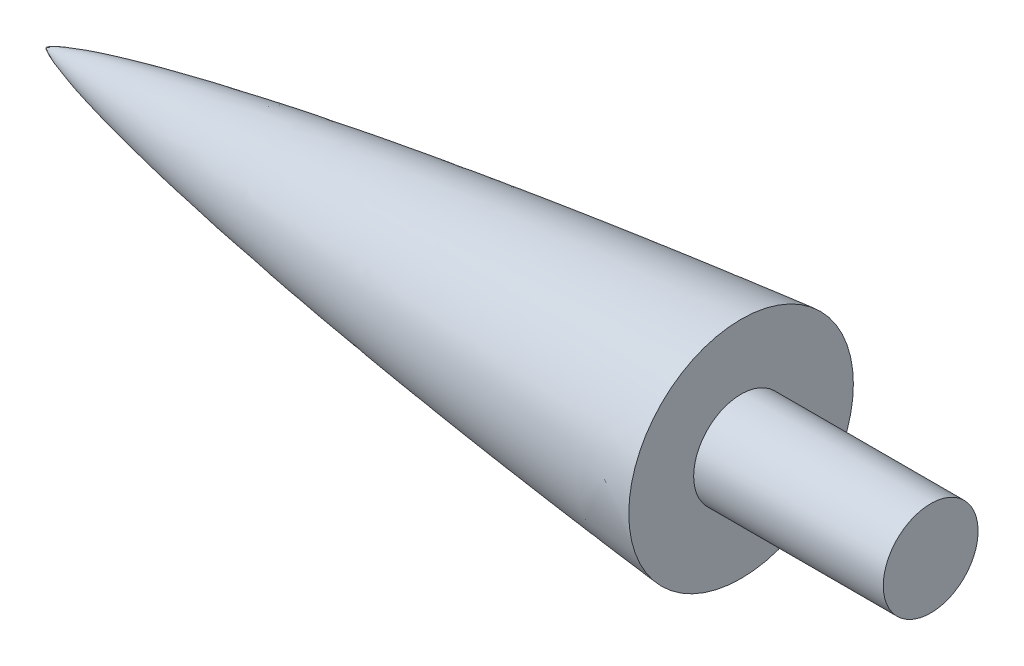
SolidWorks part; units mm, degrees
ref_plane "Front Plane" through (0, 0, 0) normal (0, 0, 1) x (1, 0, 0)
ref_plane "Top Plane" through (0, 0, 0) normal (0, 1, 0) x (1, 0, 0)
ref_plane "Right Plane" through (0, 0, 0) normal (1, 0, 0) x (0, 0, -1)
sketch "Sketch1" plane through (0, 0, 0) normal (0, 1, 0) x (1, 0, 0)
  line L0 (0, 0) -> (237, 0)
  line L1 (237, 0) -> (237, 12.7)
  line L2 (237, 12.7) -> (186.2, 12.7)
  line L3 (186.2, 12.7) -> (186.2, 30.0883)
  spline S0 degree 4 poles (0, 0) (0.0032, 0.0088) (0.0112, 0.0256) (0.0342, 0.0554) (0.0707, 0.0943) (0.1152, 0.1349) (0.1796, 0.1879) (0.2672, 0.2532) (0.3977, 0.3413) (0.6109, 0.471) (0.9573, 0.6602) (1.5471, 0.9471) (2.5834, 1.392) (4.4263, 2.0842) (7.6186, 3.1263) (13.127, 4.6859) (21.4648, 6.7263) (32.2495, 9.0388) (44.8769, 11.4582) (58.2546, 13.7926) (69.9842, 15.6855) (80.0531, 17.2205) (90.129, 18.693) (100.2175, 20.108) (110.3067, 21.4569) (120.4168, 22.7487) (128.8278, 23.7871) (134.7483, 24.4988) (139.7676, 25.0907) (144.8903, 25.6831) (149.8225, 26.247) (155.9579, 26.929) (162.3507, 27.6291) (169.6463, 28.4012) (175.5236, 29.0159) (183.0766, 29.7789) (187.4984, 30.2184) (193.3683, 30.7918) (197.7182, 31.2081) (201.3955, 31.556) (203.624, 31.7636) (204.8291, 31.8758) knots 0 0 0 0 0 0.00018 0.000359 0.000719 0.001028 0.001338 0.001964 0.002822 0.00406 0.00614 0.00956 0.015446 0.025765 0.044031 0.074194 0.125644 0.191004 0.256364 0.321724 0.387084 0.419764 0.452444 0.517804 0.583164 0.615844 0.648524 0.681204 0.697544 0.713884 0.746564 0.779244 0.811924 0.844605 0.877285 0.909965 0.932473 0.954982 0.977491 1 1 1 1 1 construction
  spline S1 degree 4 poles (0, 0) (0.0032, 0.0088) (0.0112, 0.0256) (0.0342, 0.0554) (0.0707, 0.0943) (0.1152, 0.1349) (0.1796, 0.1879) (0.2672, 0.2532) (0.3977, 0.3413) (0.6109, 0.471) (0.9573, 0.6602) (1.5471, 0.9471) (2.5834, 1.392) (4.4263, 2.0842) (7.6186, 3.1263) (13.127, 4.6859) (21.4648, 6.7263) (32.2495, 9.0388) (44.8769, 11.4582) (58.2546, 13.7926) (69.9842, 15.6855) (80.0531, 17.2205) (90.129, 18.693) (100.2175, 20.108) (110.3067, 21.4569) (120.4168, 22.7487) (128.8278, 23.7871) (134.7483, 24.4988) (139.7676, 25.0907) (144.8903, 25.6831) (149.8225, 26.247) (155.9579, 26.929) (162.3507, 27.6291) (169.6463, 28.4012) (175.5236, 29.0159) (181.6663, 29.6365) (184.663, 29.936) (186.2, 30.0883) knots 0 0 0 0 0 0.00018 0.000359 0.000719 0.001028 0.001338 0.001964 0.002822 0.00406 0.00614 0.00956 0.015446 0.025765 0.044031 0.074194 0.125644 0.191004 0.256364 0.321724 0.387084 0.419764 0.452444 0.517804 0.583164 0.615844 0.648524 0.681204 0.697544 0.713884 0.746564 0.779244 0.811924 0.844605 0.877285 0.909965 0.909965 0.909965 0.909965 0.909965
revolve "Revolve1" add sketch "Sketch1" angle 360 about L0
